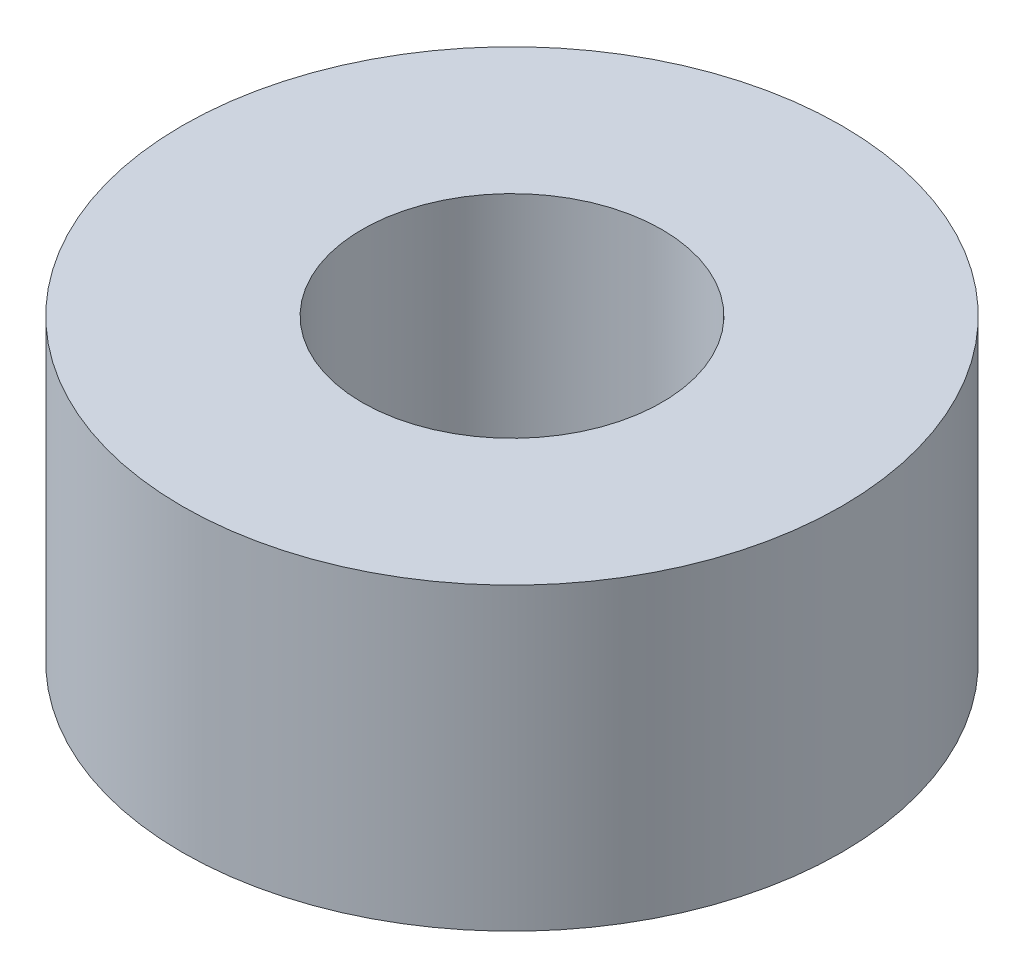
SolidWorks part; units mm, degrees
ref_plane "Front Plane" through (0, 0, 0) normal (0, 0, 1) x (1, 0, 0)
ref_plane "Top Plane" through (0, 0, 0) normal (0, 1, 0) x (1, 0, 0)
ref_plane "Right Plane" through (0, 0, 0) normal (1, 0, 0) x (0, 0, -1)
sketch "Sketch1" plane through (0, 0, 0) normal (0, 1, 0) x (1, 0, 0)
  circle A0 centre (0, 0) radius 3.9688
  circle A1 centre (0, 0) radius 8.7312
  dimension "D1" = 7.9375
  dimension "D2" = 17.4625
extrude "Boss-Extrude1" add sketch "Sketch1" along normal mid plane 7.9375 contours A0 | A1
